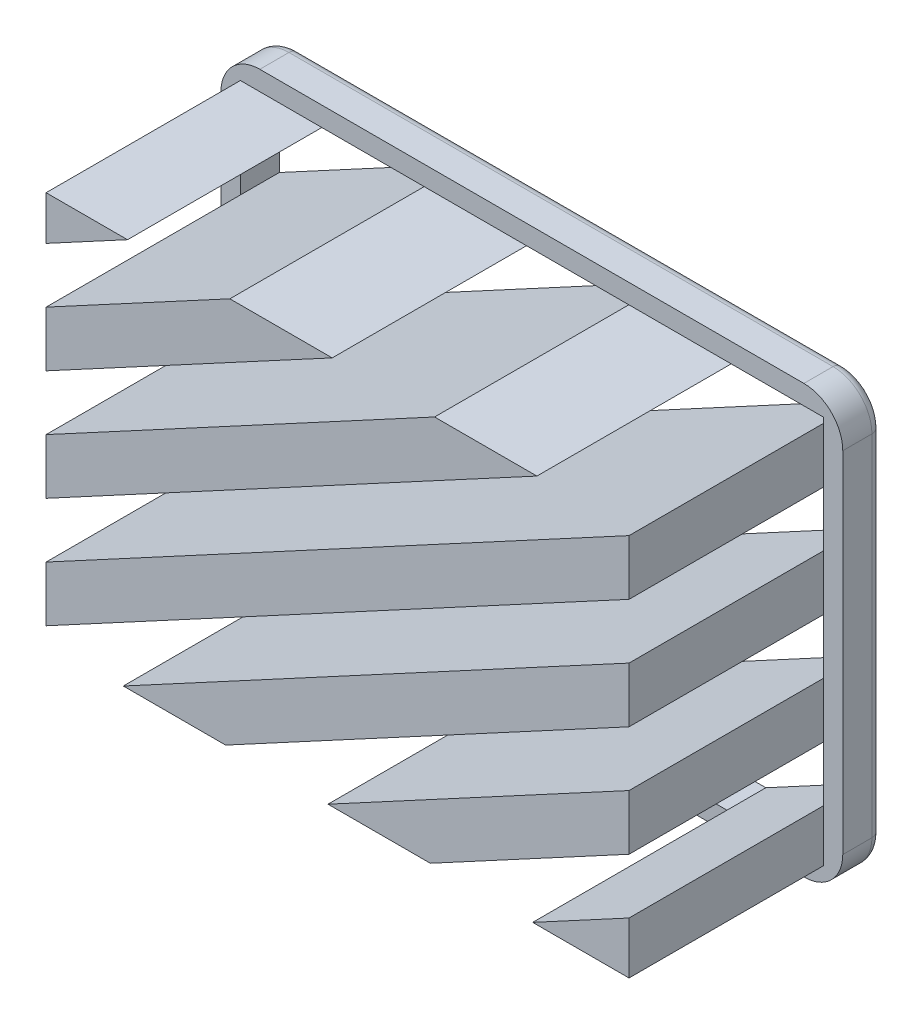
SolidWorks part; units mm, degrees
ref_plane "前视基准面" through (0, 0, 0) normal (0, 0, 1) x (1, 0, 0)
ref_plane "上视基准面" through (0, 0, 0) normal (0, 1, 0) x (1, 0, 0)
ref_plane "右视基准面" through (0, 0, 0) normal (1, 0, 0) x (0, 0, -1)
sketch "草图1" plane through (0, 0, 0) normal (0, 0, 1) x (1, 0, 0)
  line L1 (-17.5283, 8.5662) -> (17.4717, 8.5662)
  line L2 (-17.5283, 8.5662) -> (-17.5283, -16.4338)
  line L3 (-17.5283, -16.4338) -> (17.4717, -16.4338)
  line L4 (17.4717, 8.5662) -> (17.4717, -16.4338)
  dimension "D1" = 35
  dimension "D2" = 25
extrude "凸台-拉伸1" add sketch "草图1" along normal blind 12
sketch "草图2" plane through (0, 0, 0) normal (0, 0, -1) x (-1, 0, 0)
  line L0 (-17.4717, 8.5662) -> (17.5283, 8.5662) construction
  line L1 (-14.9717, 6.0662) -> (15.0283, 6.0662)
  line L2 (-14.9717, 6.0662) -> (-14.9717, -13.9338)
  line L3 (-14.9717, -13.9338) -> (15.0283, -13.9338)
  line L4 (15.0283, 6.0662) -> (15.0283, -13.9338)
  line L5 (17.5283, 8.5662) -> (17.5283, -16.4338) construction
  line L6 (17.5283, -16.4338) -> (-17.4717, -16.4338) construction
  line L7 (-17.4717, -16.4338) -> (-17.4717, 8.5662) construction
  line L8 (10.8371, 6.0662) -> (15.0283, 3.806)
  line L9 (5.5701, 6.0662) -> (15.0283, 0.9657)
  line L10 (0.3031, 6.0662) -> (15.0283, -1.8747)
  line L11 (-4.9638, 6.0662) -> (15.0283, -4.715)
  line L12 (-10.2308, 6.0662) -> (15.0283, -7.5554)
  line L13 (-15.4978, 6.0662) -> (15.0283, -10.3958)
  line L14 (-14.9717, 2.9422) -> (15.0283, -13.2361)
  line L15 (-14.9717, 0.1018) -> (11.055, -13.9338)
  line L16 (-14.9717, -2.7385) -> (5.788, -13.9338)
  line L17 (-14.9717, -5.5789) -> (0.521, -13.9338)
  line L18 (-14.9717, -8.4192) -> (-4.7459, -13.9338)
  line L19 (-14.9717, -11.2596) -> (-10.0129, -13.9338)
  dimension "D1" = 2.5
  dimension "D2" = 2.5
  dimension "D3" = 2.5
  dimension "D4" = 2.5
  dimension "D5" = 2.5
  dimension "D6" = 2.5
  dimension "D7" = 2.5
  dimension "D8" = 2.5
  dimension "D9" = 2.5
  dimension "D10" = 2.5
  dimension "D11" = 2.5
  dimension "D12" = 2.5
  dimension "D13" = 2.5
  dimension "D14" = 2.5
  dimension "D15" = 2.5
extrude "切除-拉伸1" cut sketch "草图2" against normal blind 12 contours L1 L9 L4 L8 | L1 L11 L4 L10 | L2 L13 L4 L12 L1 | L2 L15 L3 L4 L14 | L2 L17 L3 L16 | L2 L19 L3 L18
sketch "草图3" plane through (0, 0, 12) normal (0, 0, 1) x (1, 0, 0)
  line L0 (17.4717, 8.5662) -> (-17.5283, 8.5662) construction
  line L1 (14.9717, 6.0662) -> (-15.0283, 6.0662)
  line L2 (14.9717, 6.0662) -> (14.9717, -13.9338)
  line L3 (14.9717, -13.9338) -> (-15.0283, -13.9338)
  line L4 (-15.0283, 6.0662) -> (-15.0283, -13.9338)
  line M5 (14.9717, 2.9422) -> (14.9717, 0.1018)
  line M7 (-11.055, -13.9338) -> (-15.0283, -13.9338)
  line M8 (-15.0283, -13.9338) -> (-15.0283, -13.2361)
  line M10 (14.9717, -2.7385) -> (14.9717, -5.5789)
  line M12 (-0.521, -13.9338) -> (-5.788, -13.9338)
  line M14 (14.9717, 6.0662) -> (14.9717, 5.7825)
  line M16 (-15.0283, -10.3958) -> (-15.0283, -7.5554)
  line M18 (10.2308, 6.0662) -> (14.9717, 6.0662)
  line M19 (14.9717, -8.4192) -> (14.9717, -11.2596)
  line M21 (10.0129, -13.9338) -> (4.7459, -13.9338)
  line M23 (-17.5283, 8.5662) -> (-17.5283, -16.4338)
  line M24 (-17.5283, -16.4338) -> (17.4717, -16.4338)
  line M25 (17.4717, -16.4338) -> (17.4717, 8.5662)
  line M26 (17.4717, 8.5662) -> (-17.5283, 8.5662)
  line M28 (-10.8371, 6.0662) -> (-5.5701, 6.0662)
  line M30 (-15.0283, 0.9657) -> (-15.0283, 3.806)
  line M32 (-0.3031, 6.0662) -> (4.9638, 6.0662)
  line M34 (-15.0283, -4.715) -> (-15.0283, -1.8747)
extrude "切除-拉伸2" cut sketch "草图3" against normal blind 10 contours L4 L1 L2 L3 M26 M23 M24 M25 M28 M32 M18 M14 M5 M10 M19 M21 M12 M7 M8 M16 M34 M30
fillet "圆角1" radius 3 4 edges at (17.4717, -16.4338, 1) (-17.5283, -16.4338, 1) (-17.5283, 8.5662, 1) (17.4717, 8.5662, 1)
fillet "圆角2" radius 0.5 8 edges at (16.593, 7.6876, 0) (17.4717, -3.9338, 0) (16.593, -15.5551, 0) (-0.0283, -16.4338, 0) (-16.6496, -15.5551, 0) (-17.5283, -3.9338, 0) (-16.6496, 7.6876, 0) (-0.0283, 8.5662, 0)
sketch "草图4" plane through (0, 0, 2) normal (0, 0, 1) x (1, 0, 0)
  line L0 (-10.8371, 6.0662) -> (-15.0283, 6.0662) construction
  line L1 (-16.0283, 7.0662) -> (15.9717, 7.0662)
  line L2 (-16.0283, 7.0662) -> (-16.0283, -14.9338)
  line L3 (-16.0283, -14.9338) -> (15.9717, -14.9338)
  line L4 (15.9717, 7.0662) -> (15.9717, -14.9338)
  line L5 (-15.0283, 0.9657) -> (-15.0283, -1.8747) construction
  line L6 (14.9717, 0.1018) -> (14.9717, -2.7385) construction
  line L7 (14.9717, -13.9338) -> (10.0129, -13.9338) construction
  line M33 (-14.5283, -16.4338) -> (14.4717, -16.4338)
  arc M34 (14.4717, -16.4338) -> (17.4717, -13.4338) centre (14.4717, -13.4338) ccw
  line M35 (17.4717, -13.4338) -> (17.4717, 5.5662)
  arc M36 (17.4717, 5.5662) -> (14.4717, 8.5662) centre (14.4717, 5.5662) ccw
  line M37 (14.4717, 8.5662) -> (-14.5283, 8.5662)
  arc M38 (-14.5283, 8.5662) -> (-17.5283, 5.5662) centre (-14.5283, 5.5662) ccw
  line M39 (-17.5283, 5.5662) -> (-17.5283, -13.4338)
  arc M40 (-17.5283, -13.4338) -> (-14.5283, -16.4338) centre (-14.5283, -13.4338) ccw
  dimension "D1" = 1
  dimension "D2" = 1
  dimension "D3" = 1
  dimension "D4" = 1
extrude "切除-拉伸3" cut sketch "草图4" against normal blind 10 contours L1 L4 L3 L2 M40 M33 M34 M35 M36 M37 M38 M39
fillet "圆角3" radius 2 4 edges at (15.9717, 7.0662, 1) (-16.0283, 7.0662, 1) (-16.0283, -14.9338, 1) (15.9717, -14.9338, 1)
fillet "圆角4" radius 0.5 8 edges at (-0.0283, -14.9338, 0) (15.3859, -14.348, 0) (15.9717, -3.9338, 0) (15.3859, 6.4804, 0) (-0.0283, 7.0662, 0) (-15.4425, 6.4804, 0) (-16.0283, -3.9338, 0) (-15.4425, -14.348, 0)
